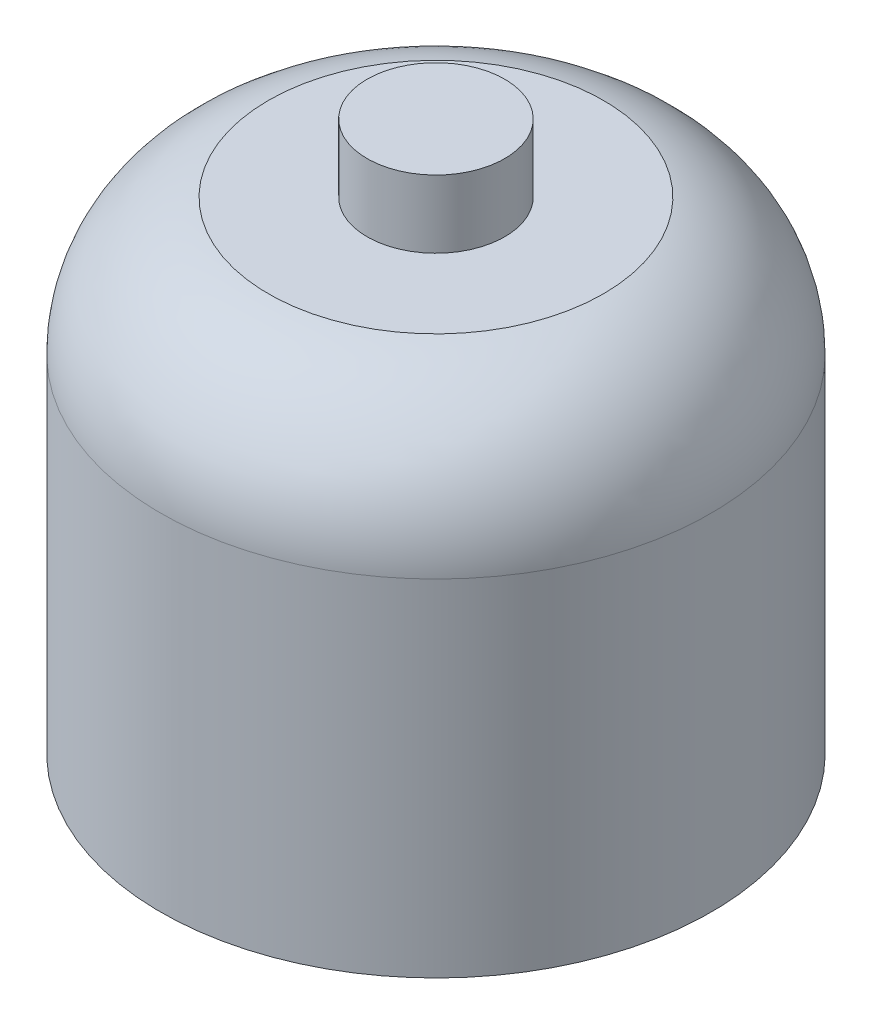
SolidWorks part; units mm, degrees
ref_plane "Front Plane" through (0, 0, 0) normal (0, 0, 1) x (1, 0, 0)
ref_plane "Top Plane" through (0, 0, 0) normal (0, 1, 0) x (1, 0, 0)
ref_plane "Right Plane" through (0, 0, 0) normal (1, 0, 0) x (0, 0, -1)
sketch "Sketch1" plane through (0, 0, 0) normal (0, 0, 1) x (1, 0, 0)
  line L0 (0, 266.537) -> (0, -433.463)
  line L1 (0, -433.463) -> (-400, -433.463)
  line L4 (-100, 266.537) -> (-100, 364.9805)
  line L5 (-100, 364.9805) -> (0, 364.9805)
  line L6 (0, 364.9805) -> (0, 266.537)
  line L8 (-243.4929, 266.537) -> (-100, 266.537)
  line L9 (-400, -433.463) -> (-400, 68.625)
  arc A2 (-400, 68.625) -> (-243.4929, 266.537) centre (-196.611, 68.625) cw
  dimension "D1" = 400
  dimension "D2" = 700
  dimension "D3" = 100
revolve "Revolve2" add sketch "Sketch1" angle 360 about L0
sketch "Sketch2" plane through (0, 0, 0) normal (0, 1, 0) x (1, 0, 0)
  line L0 (-100, 0) -> (0, 0) construction
sketch "Sketch3" plane through (0, -433.463, 0) normal (0, -1, 0) x (1, 0, 0)
  circle A1 centre (0, 0) radius 300
  dimension "D1" = 600
extrude "Cut-Extrude1" cut sketch "Sketch3" against normal blind 400
